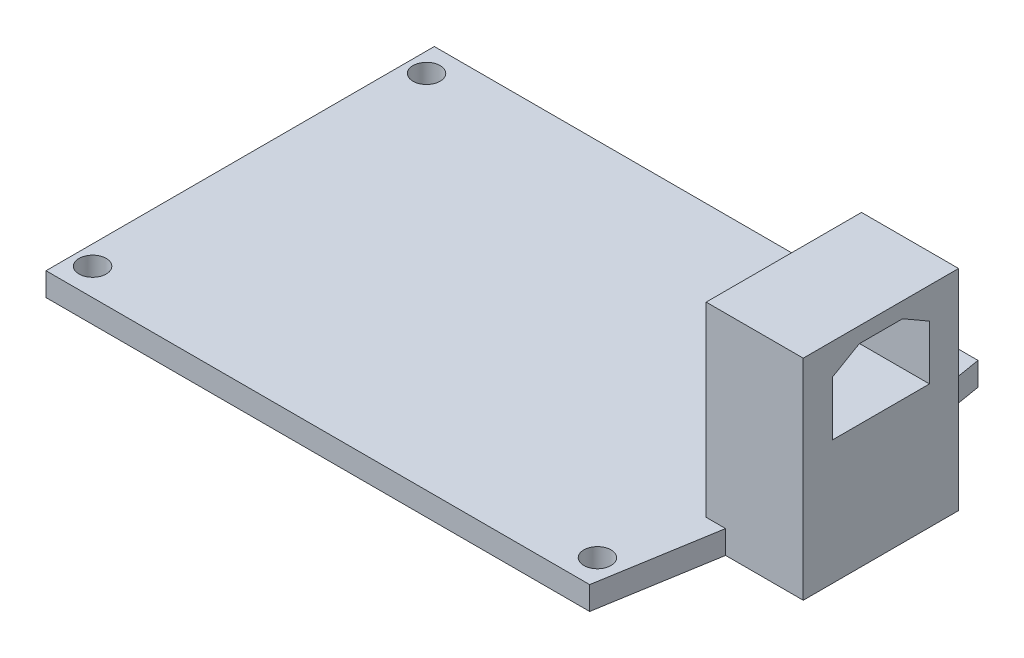
SolidWorks part; units mm, degrees
ref_plane "Front Plane" through (0, 0, 0) normal (0, 0, 1) x (1, 0, 0)
ref_plane "Top Plane" through (0, 0, 0) normal (0, 1, 0) x (1, 0, 0)
ref_plane "Right Plane" through (0, 0, 0) normal (1, 0, 0) x (0, 0, -1)
sketch "Sketch1" plane through (0, 0, 0) normal (0, 1, 0) x (1, 0, 0)
  line L0 (-35, 25) -> (35, -25) construction
  line L1 (-35, -25) -> (35, -25)
  line L2 (-35, -25) -> (-35, 25)
  line L3 (-35, 25) -> (35, 25)
  line L4 (35, -25) -> (35, 25)
  line L5 (-35, -25) -> (35, 25) construction
  point P4 (0, 0)
  dimension "D1" = 50
  dimension "D2" = 70
  dimension "D3" = 90
extrude "Boss-Extrude1" add sketch "Sketch1" along normal blind 3
sketch "Sketch2" plane through (0, 3, 0) normal (0, 1, 0) x (1, 0, 0)
  line L0 (35, -25) -> (35, 25) construction
  line L2 (-35, -25) -> (35, -25) construction
  circle A0 centre (32.5, -21.5) radius 1.75
  dimension "D1" = 3.5
  dimension "D2" = 2.5
  dimension "D3" = 3.5
extrude "Cut-Extrude1" cut sketch "Sketch2" against normal blind 10
mirror "Mirror1" about plane through (0, 0, 0) normal (0, 0, 1) of "Cut-Extrude1" second plane through (0, 0, 0) second plane normal (1, 0, 0)
sketch "Sketch4" plane through (0, 0, 0) normal (0, 1, 0) x (1, 0, 0)
  line L0 (35, -25) -> (35, 25) construction
  line L1 (35, -25) -> (35, 25)
  line L2 (35, 0) -> (37.5, 0) construction
  line L3 (37.5, -10) -> (37.5, 10)
  line L4 (37.5, -10) -> (35, -10)
  line L5 (37.5, 10) -> (35, 10)
  point P8 (37.5, 0)
  dimension "D1" = 2.5
  dimension "D2" = 20
extrude "Boss-Extrude2" add sketch "Sketch4" along normal blind 28 contours L2 L1 L4 L3 | L1 L2 L3 L5
sketch "Sketch7" plane through (0, 3, 0) normal (0, 1, 0) x (1, 0, 0)
  line L0 (35, -10) -> (35, -25)
  line L1 (37.5, -10) -> (35, -10) construction
  line L2 (37.5, -10) -> (35, -10)
  line L3 (37.5, -10) -> (35, -25)
extrude "Boss-Extrude3" add sketch "Sketch7" against normal blind 3
mirror "Mirror2" about plane through (0, 0, 0) normal (0, 0, 1) of "Boss-Extrude3"
sketch "Sketch8" plane through (37.5, 0, 0) normal (1, 0, 0) x (0, 0, -1)
  line L0 (0, 0) -> (0, 16) construction
  line L1 (-10, 0) -> (10, 0) construction
  line L2 (-6.25, 23) -> (0, 26.6084)
  line L3 (-6.25, 30) -> (6.25, 30)
  line L4 (-6.25, 30) -> (-6.25, 16)
  line L5 (-6.25, 16) -> (6.25, 16)
  line L6 (6.25, 30) -> (6.25, 16)
  line L7 (0, 26.6084) -> (6.25, 23)
  line L8 (-2.7859, 25) -> (2.7859, 25)
  line L9 (-6.25, 23) -> (6.25, 23) construction
  line L11 (-10, 28) -> (10, 28) construction
  point P8 (0, 16)
  point P14 (0, 23)
  dimension "D1" = 5
  dimension "D2" = 12.5
  dimension "D3" = 7
  dimension "D4" = 60
  dimension "D5" = 60
  dimension "D6" = 2
extrude "Cut-Extrude2" cut sketch "Sketch8" against normal blind 3 contours L7 L3 L2 L4 L5 L6
sketch "Sketch9" plane through (37.5, 0, 0) normal (1, 0, 0) x (0, 0, -1)
  line L0 (-6.25, 23) -> (-6.25, 16) construction
  line L1 (-6.25, 16) -> (6.25, 16) construction
  line L2 (6.25, 23) -> (6.25, 16) construction
  line L3 (2.7859, 25) -> (6.25, 23) construction
  line L4 (-2.7859, 25) -> (2.7859, 25) construction
  line L5 (-6.25, 23) -> (-2.7859, 25) construction
  line L6 (-6.25, 23) -> (-6.25, 16)
  line L7 (-6.25, 16) -> (6.25, 16)
  line L8 (6.25, 23) -> (6.25, 16)
  line L9 (2.7859, 25) -> (6.25, 23)
  line L10 (-2.7859, 25) -> (2.7859, 25)
  line L11 (-6.25, 23) -> (-2.7859, 25)
  line L12 (-6.75, 15.5) -> (6.75, 15.5)
  line L13 (6.75, 23.2887) -> (6.75, 15.5)
  line L14 (2.9199, 25.5) -> (6.75, 23.2887)
  line L15 (-2.9199, 25.5) -> (2.9199, 25.5)
  line L16 (-6.75, 23.2887) -> (-2.9199, 25.5)
  line L17 (-6.75, 23.2887) -> (-6.75, 15.5)
  dimension "D1" = 0.5
extrude "Boss-Extrude4" add sketch "Sketch9" along normal blind 10
sketch "Sketch10" plane through (37.5, 0, 0) normal (1, 0, 0) x (0, 0, -1)
  line L0 (-6.75, 23.2887) -> (-6.75, 15.5) construction
  line L1 (-2.9199, 25.5) -> (-6.75, 23.2887) construction
  line L2 (2.9199, 25.5) -> (-2.9199, 25.5) construction
  line L3 (6.75, 23.2887) -> (2.9199, 25.5) construction
  line L4 (6.75, 15.5) -> (6.75, 23.2887) construction
  line L5 (-6.75, 15.5) -> (6.75, 15.5) construction
  line L6 (-6.75, 23.2887) -> (-6.75, 15.5)
  line L7 (-2.9199, 25.5) -> (-6.75, 23.2887)
  line L8 (2.9199, 25.5) -> (-2.9199, 25.5)
  line L9 (6.75, 23.2887) -> (2.9199, 25.5)
  line L10 (6.75, 15.5) -> (6.75, 23.2887)
  line L11 (-6.75, 15.5) -> (6.75, 15.5)
  line L12 (-10, 28) -> (-10, 3) construction
  line L13 (-10, 0) -> (-10, 3) construction
  line L14 (10, 0) -> (10, 3) construction
  line L15 (10, 28) -> (10, 3) construction
  line L16 (-10, 28) -> (-10, 3)
  line L17 (-10, 0) -> (-10, 3)
  line L18 (10, 0) -> (10, 3)
  line L19 (10, 28) -> (10, 3)
  line L20 (-10, 27) -> (10, 27)
  point P14 (0, 27)
  point P15 (0, 25.5)
  line M1 (-10, 0) -> (10, 0)
  line M2 (10, 0) -> (10, 3)
  line M3 (10, 3) -> (10, 28)
  line M6 (-10, 3) -> (-10, 0)
  line M7 (-6.75, 15.5) -> (-6.75, 23.2887)
  line M8 (-6.75, 23.2887) -> (-2.9199, 25.5)
  line M9 (-2.9199, 25.5) -> (2.9199, 25.5)
  line M10 (2.9199, 25.5) -> (6.75, 23.2887)
  line M11 (6.75, 23.2887) -> (6.75, 15.5)
  line M12 (6.75, 15.5) -> (-6.75, 15.5)
  dimension "D1" = 1.5
extrude "Boss-Extrude5" add sketch "Sketch10" along normal blind 10 contours L20 L16 M6 M1 M2 M3 M12 M7 M8 M9 M10 M11
sketch "Sketch11" plane through (37.5, 0, 0) normal (1, 0, 0) x (0, 0, -1)
  line L0 (10, 28) -> (10, 27) construction
  line L1 (-10, 27) -> (10, 27) construction
  line L2 (-10, 28) -> (10, 28) construction
  line L3 (-10, 28) -> (-10, 27) construction
  line L4 (10, 28) -> (10, 27)
  line L5 (-10, 27) -> (10, 27)
  line L6 (-10, 28) -> (10, 28)
  line L7 (-10, 28) -> (-10, 27)
extrude "Cut-Extrude3" cut sketch "Sketch11" against normal blind 10
